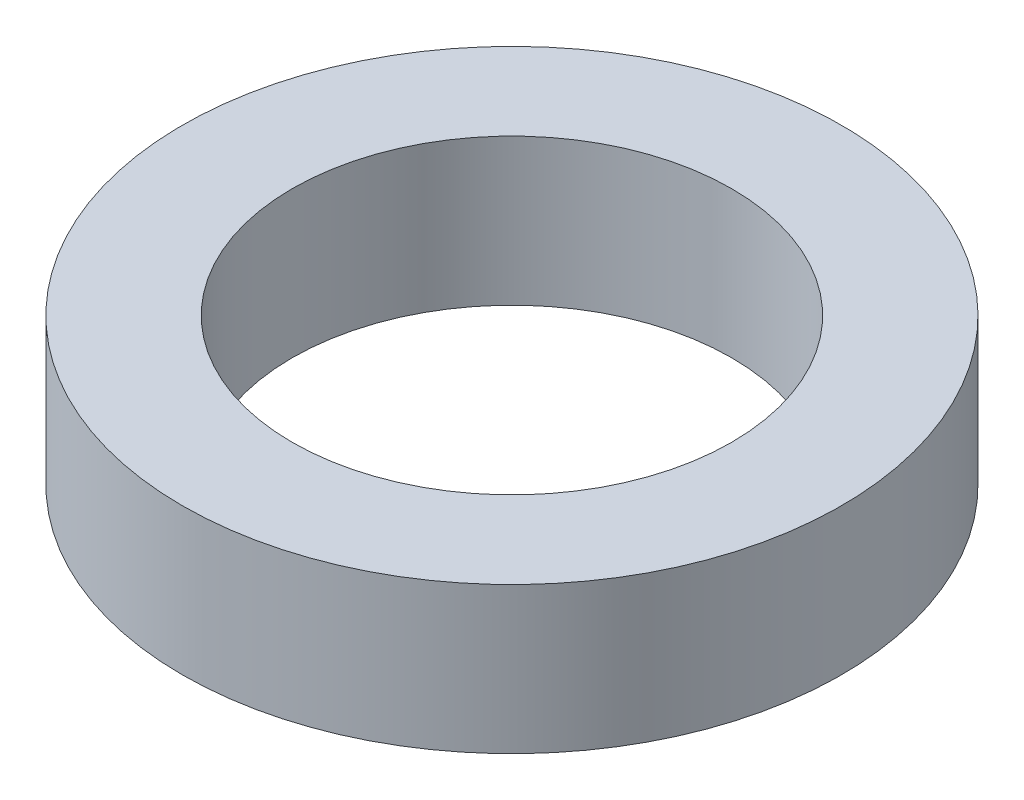
SolidWorks part; units mm, degrees
ref_plane "前视基准面" through (0, 0, 0) normal (0, 0, 1) x (1, 0, 0)
ref_plane "上视基准面" through (0, 0, 0) normal (0, 1, 0) x (1, 0, 0)
ref_plane "右视基准面" through (0, 0, 0) normal (1, 0, 0) x (0, 0, -1)
other "Configuration Table"
sketch "草图1" plane through (0, 0, 0) normal (0, 1, 0) x (1, 0, 0)
  circle A0 centre (0, 0) radius 3
  circle A1 centre (0, 0) radius 4.5
  dimension "D1" = 6
  dimension "D2" = 9
extrude "凸台-拉伸1" add sketch "草图1" along normal blind 2
